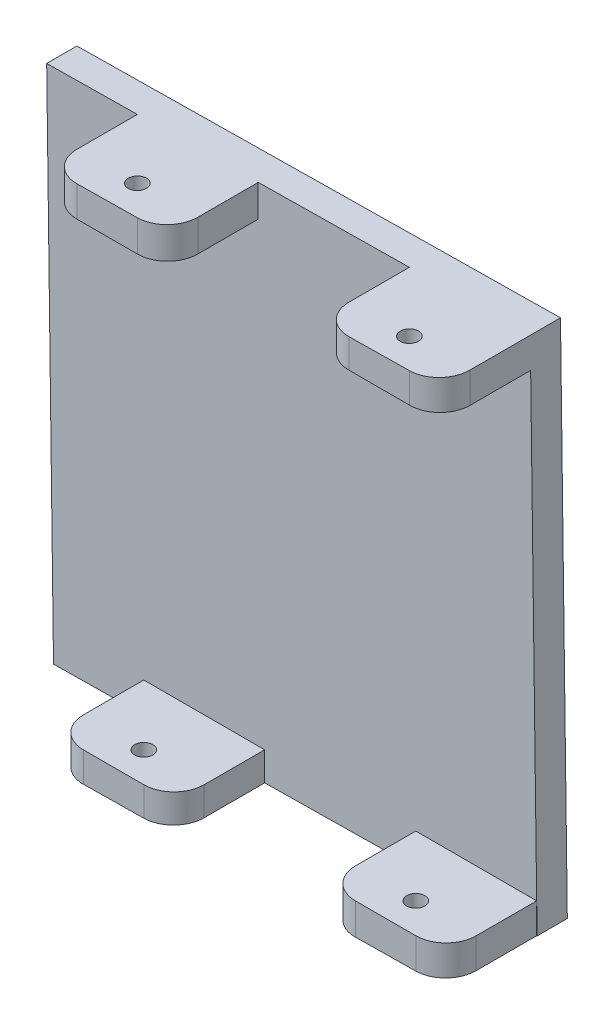
SolidWorks part; units mm, degrees
ref_plane "Front Plane" through (0, 0, 0) normal (0, 0, 1) x (1, 0, 0)
ref_plane "Top Plane" through (0, 0, 0) normal (0, 1, 0) x (1, 0, 0)
ref_plane "Right Plane" through (0, 0, 0) normal (1, 0, 0) x (0, 0, -1)
sketch "Sketch1" plane through (0, 0, 0) normal (0, 0, 1) x (1, 0, 0)
  line L0 (-47.0269, 0) -> (32.9731, 1.0576)
  line L1 (32.9731, 1.0576) -> (31.8428, 86.5576)
  line L2 (31.8428, 86.5576) -> (-48.1572, 85.5)
  line L3 (-48.1572, 85.5) -> (-47.0269, 0)
  dimension "D1" = 85.5
  dimension "D2" = 80
extrude "Boss-Extrude1" add sketch "Sketch1" along normal blind 5
sketch "Sketch2" plane through (0, 0, 0) normal (0, 0, 1) x (1, 0, 0)
  line L0 (-33.1572, 85.6983) -> (-33.1572, 80.6983)
  line L1 (31.8428, 86.5576) -> (-48.1572, 85.5) construction
  line L2 (-33.1572, 80.6983) -> (-13.1572, 80.6983)
  line L3 (-13.1572, 80.6983) -> (-13.1572, 85.9627)
  line L4 (-13.1572, 85.9627) -> (-33.1572, 85.6983)
  line L7 (11.8428, 86.2932) -> (11.8428, 81.558)
  line L8 (11.8428, 81.558) -> (31.9089, 81.558)
  line L9 (31.9089, 81.558) -> (31.8428, 86.5576)
  line L10 (32.9731, 1.0576) -> (31.8428, 86.5576) construction
  line L12 (31.8428, 86.5576) -> (11.8428, 86.2932)
  line L13 (-32.093, 0.1974) -> (-32.093, 5.1974)
  line L14 (-47.0269, 0) -> (32.9731, 1.0576) construction
  line L15 (-32.093, 5.1974) -> (-12.093, 5.1974)
  line L16 (-12.093, 5.1974) -> (-12.093, 0.4618)
  line L17 (-12.093, 0.4618) -> (-32.093, 0.1974)
  line L18 (12.907, 0.7923) -> (12.907, 6.0567)
  line L19 (12.907, 6.0567) -> (32.907, 6.0567)
  line L20 (32.907, 6.0567) -> (32.907, 1.0567)
  line L21 (32.907, 1.0567) -> (12.907, 0.7923)
  point P22 (0, 0)
  point P25 (0, 0)
  point P26 (0, 0)
  point P27 (0, 0)
  point P28 (0, 0)
  point P29 (0, 0)
  point P30 (0, 0)
  point P31 (0, 0)
  point P32 (31.5826, 100.9013)
  point P33 (0, 0)
  point P35 (0, 0)
  point P36 (0, 0)
  dimension "D1" = 5
  dimension "D2" = 20
  dimension "D3" = 5
  dimension "D4" = 20
  dimension "D5" = 0
  dimension "D6" = 25
  dimension "D7" = 5
  dimension "D8" = 5
  dimension "D9" = 20
  dimension "D10" = 0
  dimension "D11" = 25
  dimension "D12" = 20
extrude "Boss-Extrude2" add sketch "Sketch2" along normal blind 20
fillet "Fillet1" radius 5 8 edges at (32.907, 3.5567, 20) (12.907, 3.4245, 20) (-12.093, 2.8296, 20) (-32.093, 2.6974, 20) (31.8759, 84.0578, 20) (11.8428, 83.9256, 20) (-13.1572, 83.3305, 20) (-33.1572, 83.1983, 20)
sketch "Sketch5" plane through (-1.1385, 86.1216, 0) normal (-0.0132, 0.9999, 0) x (0.9999, 0.0132, 0)
  line L0 (-32.0215, -15) -> (-32.0215, -5) construction
  line L1 (-32.0215, -5) -> (-47.0228, -5) construction
  line L3 (12.9824, -15) -> (12.9824, -5) construction
  point P0 (-22.0215, -15)
  point P1 (22.9824, -15)
  dimension "D1" = 10
  dimension "D2" = 10
  dimension "D4" = 10
hole_wizard "Ø3.0 (3) Diameter Hole1" positions "Sketch5" profile "Sketch7" hole size "Ø3.0" standard "ANSI Metric" end condition through all
sketch "Sketch7" plane through (-23.1581, 85.8305, 15) normal (0, 0, 1) x (-0.9999, -0.0132, 0)
  line L0 (0, 0) -> (0, 86.5649)
  line L1 (0, 86.5649) -> (1.5, 86.5649)
  line L2 (1.5, 86.5649) -> (1.5, 0)
  line L5 (1.5, 0) -> (0, 0)
  line L11 (0, -6.35) -> (0, 107.95) construction
  dimension "Thru Hole Dia." = 3
  dimension "Thru Hole Depth" = 86.5649
